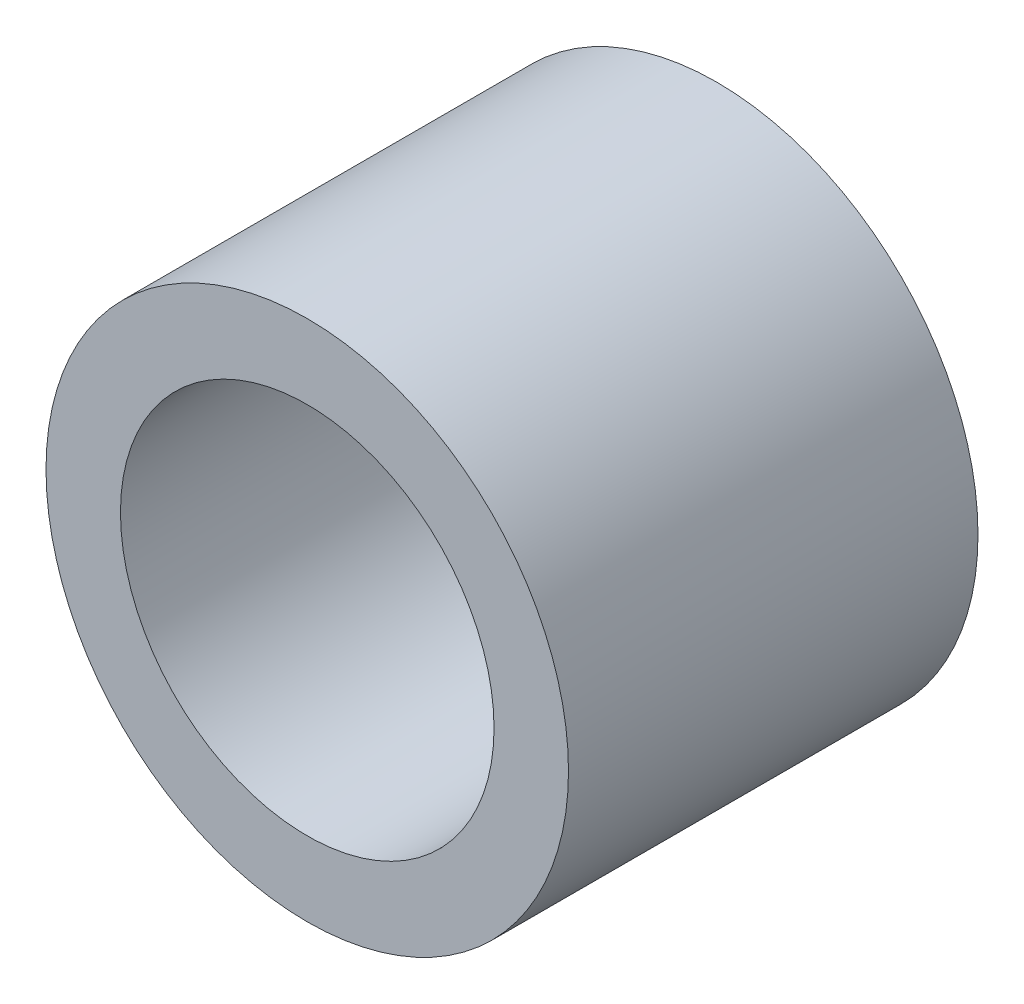
SolidWorks part; units mm, degrees
material "Commercial Bronze, UNS C22000 (90-10 Bronze)"
ref_plane "Front Plane" through (0, 0, 0) normal (0, 0, 1) x (1, 0, 0)
ref_plane "Top Plane" through (0, 0, 0) normal (0, 1, 0) x (1, 0, 0)
ref_plane "Right Plane" through (0, 0, 0) normal (1, 0, 0) x (0, 0, -1)
sketch "Sketch1" plane through (0, 0, 0) normal (0, 0, 1) x (1, 0, 0)
  circle A0 centre (0, 0) radius 15.053
  circle A1 centre (0, 0) radius 21.053
  dimension "D1" = 6
  dimension "D2" = 30.106
extrude "Boss-Extrude1" add sketch "Sketch1" along normal blind 33
